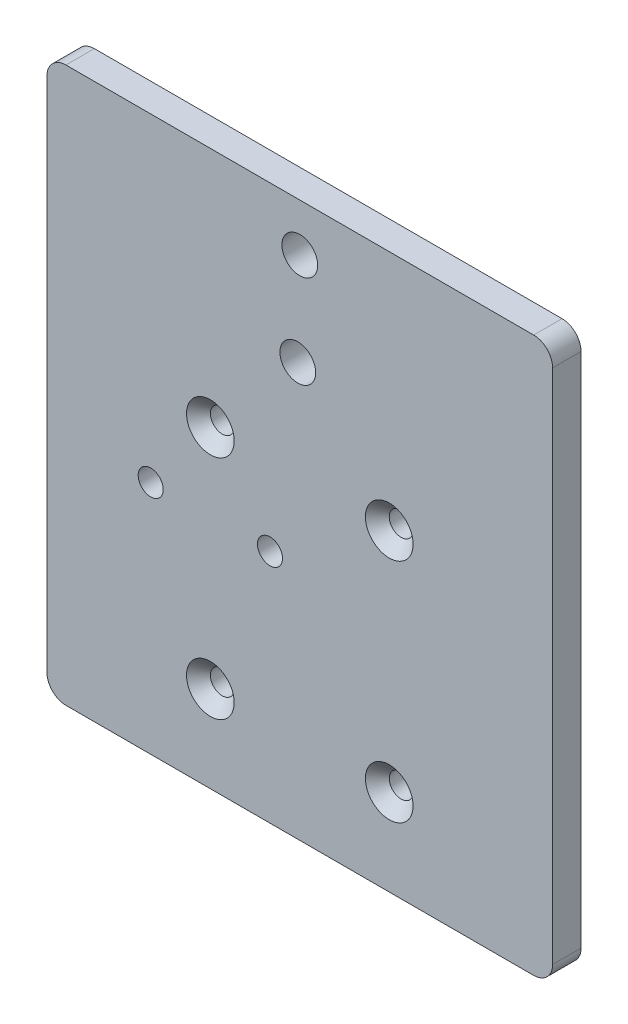
SolidWorks part; units mm, degrees
ref_plane "Front Plane" through (0, 0, 0) normal (0, 0, 1) x (1, 0, 0)
ref_plane "Top Plane" through (0, 0, 0) normal (0, 1, 0) x (1, 0, 0)
ref_plane "Right Plane" through (0, 0, 0) normal (1, 0, 0) x (0, 0, -1)
sketch "Sketch1" plane through (0, 0, 0) normal (0, 0, 1) x (1, 0, 0)
  line L1 (-42.4, -33.5) -> (42.4, -33.5)
  line L2 (-42.4, -33.5) -> (-42.4, 59.5)
  line L3 (-42.4, 59.5) -> (42.4, 59.5)
  line L4 (42.4, -33.5) -> (42.4, 59.5)
  line L6 (10.75, -23.5) -> (19.4, -23.5) construction
  line L7 (19.4, 23.5) -> (-19.4, 23.5) construction
  circle A0 centre (-15, 19) radius 2
  circle A1 centre (15, 19) radius 0.1985
  circle A2 centre (15, 19) radius 2
  circle A3 centre (-15, -19) radius 2
  circle A4 centre (15, -19) radius 2
  point P8 (15.075, -23.5)
  dimension "D5" = 4
  dimension "D6" = 4
  dimension "D7" = 4
  dimension "D8" = 4
  dimension "D1" = 27.4
  dimension "D2" = 27.4
  dimension "D3" = 10
  dimension "D4" = 36
extrude "Boss-Extrude1" add sketch "Sketch1" along normal blind 4.7625 contours L1 L4 L3 L2 A4 A3 A2 A0
fillet "Fillet1" radius 3.18 4 edges at (-42.4, -33.5, 2.3813) (42.4, -33.5, 2.3813) (42.4, 59.5, 2.3813) (-42.4, 59.5, 2.3813)
sketch "Sketch2" plane through (0, 0, 4.7625) normal (0, 0, 1) x (1, 0, 0)
  line L0 (-39.22, 59.5) -> (39.22, 59.5) construction
  point P0 (-15, 33.55)
  point P1 (-14.6008, 9.8)
  dimension "D1" = 25.95
sketch "Sketch8" plane through (0, 0, 0) normal (0, 0, -1) x (-1, 0, 0)
  point P0 (0, 51.5)
  point P1 (0.3365, 35.75)
hole_wizard "Ø6.0 (6) Diameter Hole1" positions "Sketch10" profile "Sketch9" hole size "Ø6.0" standard "ANSI Metric"
sketch "Sketch10" plane through (0, 0, 0) normal (0, 0, -1) x (-1, 0, 0)
  point P0 (0, 51.5)
  point P3 (0.3365, 35.75)
sketch "Sketch9" plane through (0, 51.5, 0) normal (1, 0, 0) x (0, 1, 0)
  line L0 (0, 0) -> (0, 25.8026)
  line L1 (0, 25.8026) -> (3, 24)
  line L2 (3, 24) -> (3, 0)
  line L5 (3, 0) -> (0, 0)
  line L10 (0, 25.8026) -> (-3, 24) construction
  line L11 (0, -6.35) -> (0, 107.95) construction
  dimension "Hole Dia." = 6
  dimension "Hole Depth" = 24
  dimension "Drill Angle" = 118
chamfer "Chamfer1" distance 2 angle 45 4 edges at (-13, -19, 4.7625) (17, -19, 4.7625) (17, 19, 4.7625) (-13, 19, 4.7625)
sketch "Sketch23" plane through (0, 0, 4.7625) normal (0, 0, 1) x (1, 0, 0)
  line L0 (-42.4, -30.32) -> (-42.4, 56.32) construction
  line L1 (-39.22, -33.5) -> (39.22, -33.5) construction
  point P0 (-25, 5.98)
  point P1 (-5, 5.98)
  dimension "D1" = 20
  dimension "D2" = 17.4
  dimension "D3" = 39.48
hole_wizard "M5x0.8 Tapped Hole1" positions "Sketch29" profile "Sketch28" tap size "M5x0.8" standard "ANSI Metric"
sketch "Sketch29" plane through (0, 0, 4.7625) normal (0, 0, 1) x (1, 0, 0)
  point P0 (-70.2084, 8.3416)
  point P2 (-70.2084, 8.3416)
  point P4 (-69.847, 8.3416)
  point P6 (-25, 5.9821)
  point P8 (-5, 5.9821)
sketch "Sketch28" plane through (-70.2084, 8.3416, 4.7625) normal (1, 0, 0) x (0, -1, 0)
  line L0 (0, 0) -> (0, 15.2618)
  line L1 (0, 15.2618) -> (2.1, 14)
  line L2 (2.1, 14) -> (2.1, 0)
  line L5 (2.1, 0) -> (0, 0)
  line L10 (0, 15.2618) -> (-2.1, 14) construction
  line L11 (0, -6.35) -> (0, 107.95) construction
  dimension "Tap Drill Dia." = 4.2
  dimension "Tap Drill Depth" = 14
  dimension "Drill Angle" = 118
cosmetic thread "Hole Thread9" parameters "D1"=4.7625, "D2"=5
cosmetic thread "Hole Thread10" parameters "D1"=4.7625, "D2"=5
